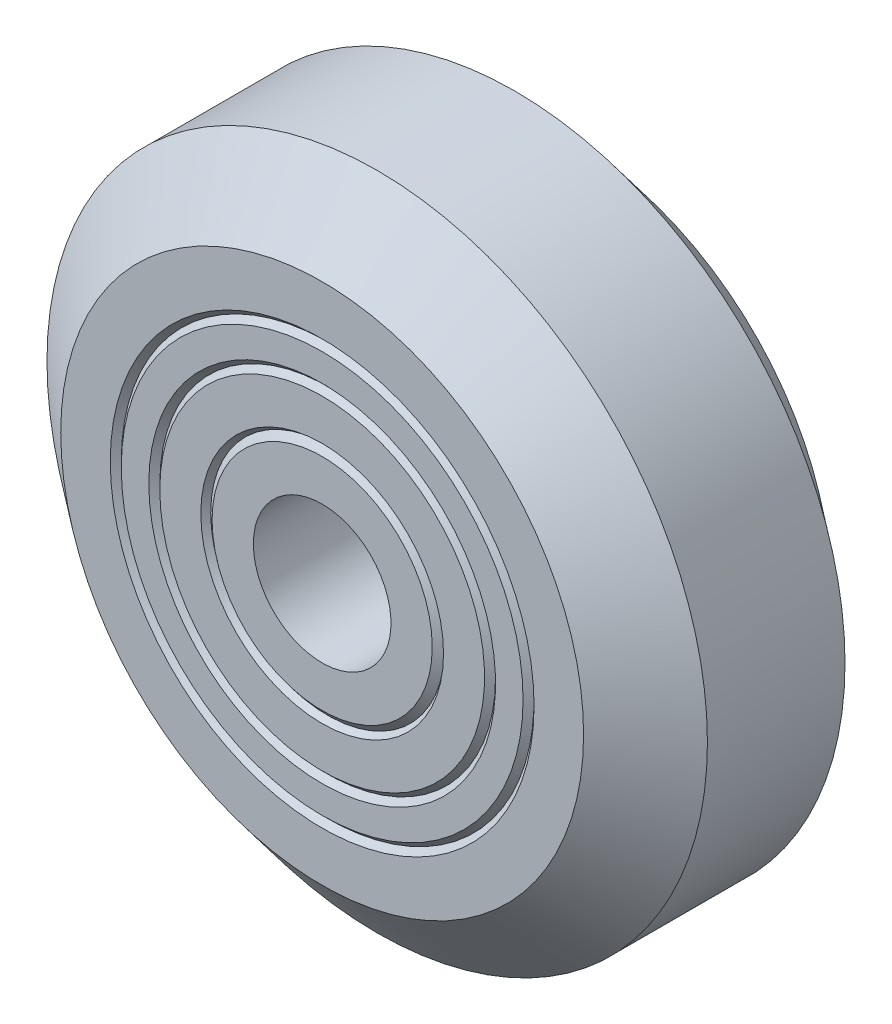
SolidWorks part; units mm, degrees
ref_plane "Front Plane" through (0, 0, 0) normal (0, 0, 1) x (1, 0, 0)
ref_plane "Top Plane" through (0, 0, 0) normal (0, 1, 0) x (1, 0, 0)
ref_plane "Right Plane" through (0, 0, 0) normal (1, 0, 0) x (0, 0, -1)
sketch "Sketch1" plane through (0, 0, 0) normal (1, 0, 0) x (0, 0, -1)
  line L0 (0, 0) -> (-4.5, 0) construction
  line L1 (-4.5, 7.3) -> (-4.5, 6.3)
  line L2 (-2.5, 12) -> (0, 12)
  line L3 (-4.5, 9.5) -> (-2.5, 12)
  line L4 (0, 12) -> (0, 7.5) construction
  line L5 (-4.5, 7.5) -> (-4.3, 7.5) construction
  line L6 (-4.3, 7.5) -> (-4.5, 7.7)
  line L7 (-4.3, 7.5) -> (-4.5, 7.3)
  line L8 (-4.5, 7.7) -> (-4.5, 9.5)
  line L9 (-4.5, 6.3) -> (-4.3, 6.1)
  line L10 (-4.3, 6.1) -> (-4.5, 5.9)
  line L11 (0, 2.5) -> (-4.5, 2.5)
  line L12 (-4.5, 4) -> (-4.3, 4.25)
  line L13 (0, 2.5) -> (0, 12)
  line L14 (-4.5, 2.5) -> (-4.5, 4)
  line L15 (-4.3, 4.25) -> (-4.5, 4.41)
  line L16 (-4.5, 4.41) -> (-4.5, 5.9)
  point P4 (-4.5, 12)
  dimension "D1" = 2.5
  dimension "D2" = 2
  dimension "D3" = 2.5
revolve "Revolve1" add sketch "Sketch1" angle 360 about L0
mirror "Mirror1" about plane through (0, 2.5, 0) normal (0, 0, -1) of bodies 101
